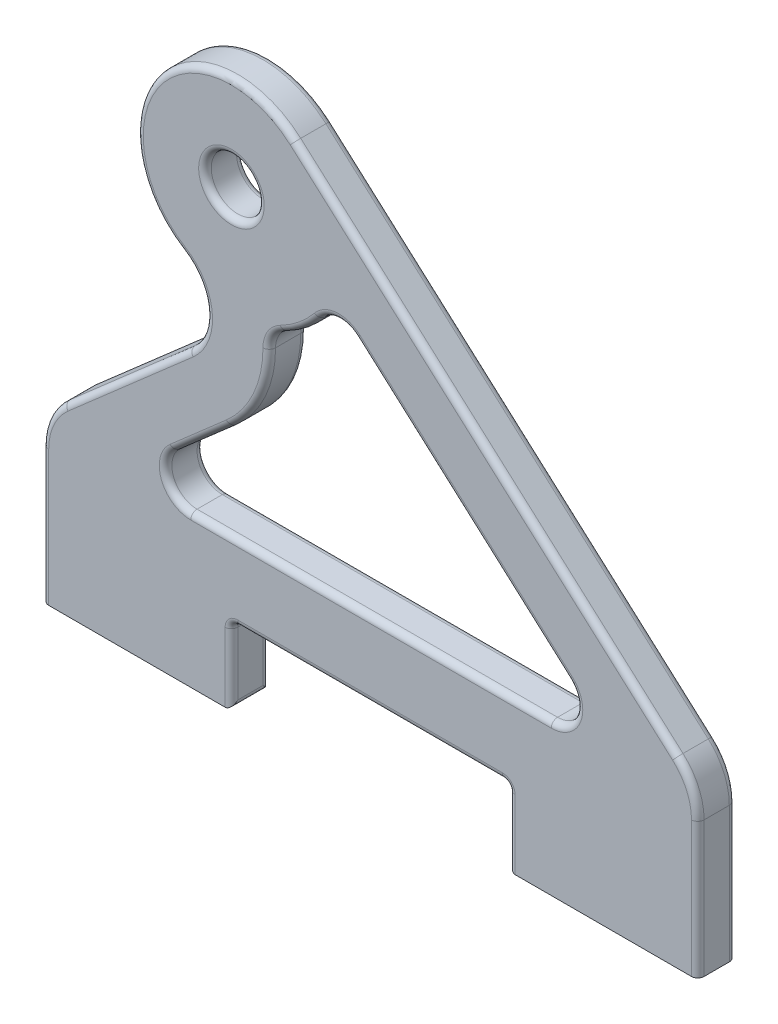
SolidWorks part; units mm, degrees
ref_plane "Front Plane" through (0, 0, 0) normal (0, 0, 1) x (1, 0, 0)
ref_plane "Top Plane" through (0, 0, 0) normal (0, 1, 0) x (1, 0, 0)
ref_plane "Right Plane" through (0, 0, 0) normal (1, 0, 0) x (0, 0, -1)
sketch "Sketch1" plane through (0, 0, 0) normal (0, 0, 1) x (1, 0, 0)
  line L0 (0, 0) -> (15, 0)
  line L1 (15, 0) -> (15, 6)
  line L2 (15, 6) -> (37, 6)
  line L3 (37, 6) -> (37, 0)
  line L4 (37, 0) -> (52, 0)
  line L5 (52, 0) -> (52, 13)
  line L6 (0, 13) -> (11.6339, 23.1789)
  line L7 (52, 13) -> (19.9969, 41.5929)
  line L8 (0, 0) -> (0, 13)
  circle A0 centre (15, 36) radius 2.1
  arc A1 (19.9969, 41.5929) -> (11.087, 29.6017) centre (15, 36) ccw
  arc A2 (11.6339, 23.1789) -> (11.087, 29.6017) centre (9, 26.1893) ccw
  dimension "D5" = 4.2
  dimension "D7" = 15
  dimension "D10" = 8
  dimension "D1" = 15
  dimension "D2" = 6
  dimension "D3" = 22
  dimension "D4" = 15
  dimension "D6" = 36
  dimension "D8" = 15
  dimension "D9" = 13
  dimension "D11" = 9
extrude "Boss-Extrude1" add sketch "Sketch1" along normal blind 3
fillet "Fillet1" radius 5 2 edges at (52, 13, 1.5) (0, 13, 1.5)
sketch "Sketch3" plane through (0, 0, 0) normal (0, 0, -1) x (-1, 0, 0)
  line L2 (-47, 10.7623) -> (-16.6656, 37.8643)
  line L3 (-41.7068, 15.4914) -> (-24.8601, 30.543)
  line L5 (-14.9263, 19.4159) -> (-5, 10.731)
  line L6 (-14.9263, 19.4159) -> (-10.4566, 15.5052)
  line L15 (-15, 12) -> (-37, 12)
  line L16 (-11.7736, 12) -> (-40.3743, 12)
  arc A0 (-19.0909, 27.9835) -> (-18, 26.1997) centre (-20, 26.202) cw
  arc A1 (-21.9771, 30.3149) -> (-19.0909, 27.9835) centre (-15, 36) ccw
  arc A2 (-13.6957, 33.8672) -> (-14.9263, 19.4159) centre (-9, 26.1893) ccw
  arc A3 (-18, 26.1997) -> (-14.9263, 19.4159) centre (-9, 26.1893) ccw
  arc A4 (-24.8601, 30.543) -> (-21.9771, 30.3149) centre (-23.5276, 29.0516) cw
  arc A5 (-10.4566, 15.5052) -> (-11.7736, 12) centre (-11.7736, 14) cw
  arc A6 (-40.3743, 12) -> (-41.7068, 15.4914) centre (-40.3743, 14) cw
  dimension "D4" = 18
  dimension "D6" = 2
  dimension "D1" = 5
  dimension "D2" = 5
  dimension "D3" = 6
  dimension "D5" = 5
extrude "Cut-Extrude1" cut sketch "Sketch3" against normal blind 10
fillet "Fillet2" radius 0.5 46 edges at (23.3698, 31.0454, 0) (20.6555, 28.9989, 0) (18.2938, 27.2455, 0) (17.1978, 22.4749, 0) (12.6914, 17.4605, 0) (9.9013, 13.2966, 0) (26.0739, 12, 0) (42.2428, 13.2869, 0) (42.2428, 13.2869, 3) (26.0739, 12, 3) (9.9013, 13.2966, 3) (12.6914, 17.4605, 3) (17.1978, 22.4749, 3) (18.2938, 27.2455, 3) (20.6555, 28.9989, 3) (23.3698, 31.0454, 3) (52, 5.3811, 3) (51.5638, 12.8048, 3) (35.1641, 28.0419, 3) (8.98, 40.4732, 3) (0, 5.3655, 3) (0.4469, 12.7972, 3) (6.6708, 18.8365, 3) (52, 5.3811, 0) (51.5638, 12.8048, 0) (35.1641, 28.0419, 0) (8.98, 40.4732, 0) (0, 5.3655, 0) (0.4469, 12.7972, 0) (6.6708, 18.8365, 0) (26, 6, 3) (26, 6, 0) (15, 0, 1.5) (15, 3, 3) (15, 6, 1.5) (15, 3, 0) (37, 6, 1.5) (37, 3, 3) (37, 0, 1.5) (37, 3, 0) (33.2835, 23.0172, 0) (33.2835, 23.0172, 3) (17.1, 36, 0) (17.1, 36, 3) (12.9856, 26.5287, 3) (12.9856, 26.5287, 0)
